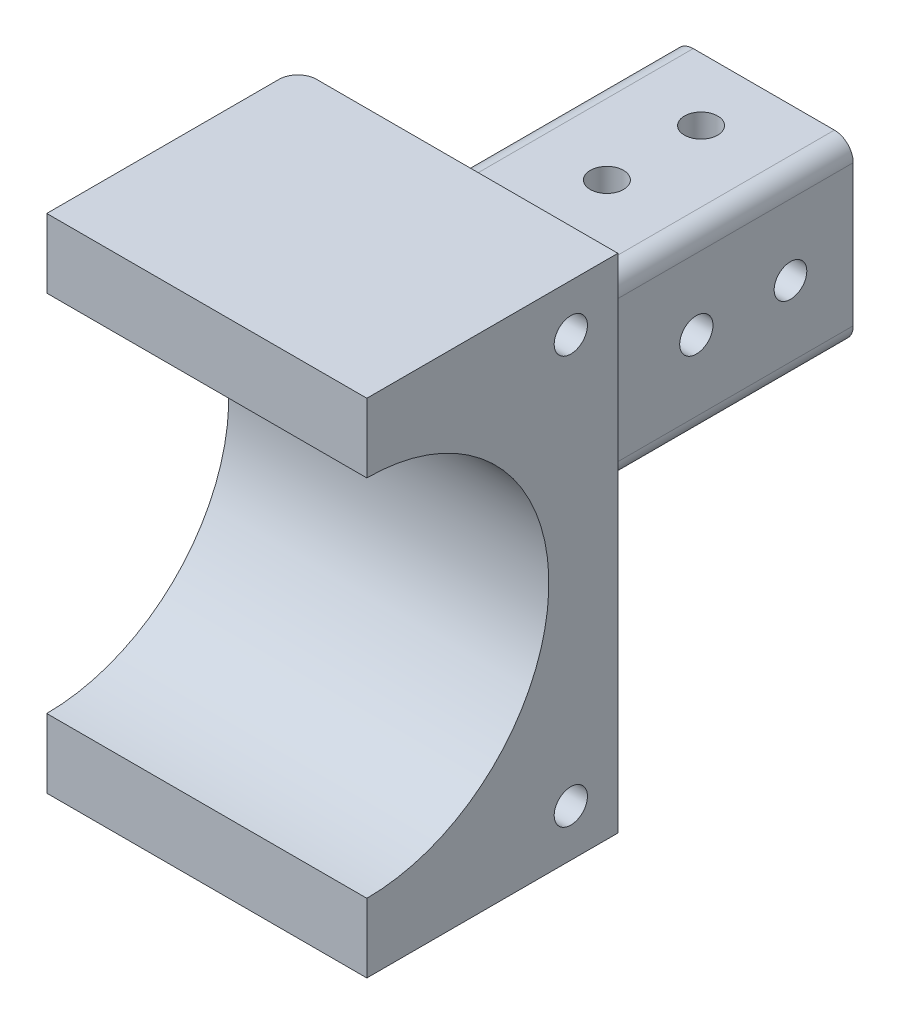
SolidWorks part; units mm, degrees
ref_plane "前视基准面" through (0, 0, 0) normal (0, 0, 1) x (1, 0, 0)
ref_plane "上视基准面" through (0, 0, 0) normal (0, 1, 0) x (1, 0, 0)
ref_plane "右视基准面" through (0, 0, 0) normal (1, 0, 0) x (0, 0, -1)
other "Configuration Table"
sketch "草图1" plane through (0, 0, 0) normal (0, 0, 1) x (1, 0, 0)
  line L0 (-14.25, 14.25) -> (14.25, 14.25)
  line L1 (-10.25, -10.25) -> (10.25, -10.25)
  line L2 (-10.25, -10.25) -> (-10.25, 10.25)
  line L3 (-10.25, 10.25) -> (10.25, 10.25)
  line L4 (10.25, -10.25) -> (10.25, 10.25)
  line L5 (-10.25, -10.25) -> (10.25, 10.25) construction
  line L6 (-10.25, 10.25) -> (10.25, -10.25) construction
  line L7 (14.25, -14.25) -> (14.25, 14.25)
  line L8 (-14.25, -14.25) -> (14.25, -14.25)
  line L9 (-14.25, -14.25) -> (-14.25, 14.25)
  point P0 (0, 0)
  dimension "D1" = 20.5
  dimension "D2" = 20.5
  dimension "D3" = 4
extrude "凸台-拉伸1" add sketch "草图1" along normal blind 30
sketch "草图2" plane through (-14.25, 0, 0) normal (-1, 0, 0) x (0, 0, 1)
  line L0 (30, 0) -> (70, 0)
  line L1 (30, 14.25) -> (30, -14.25) construction
  line L3 (110, -40) -> (30, -40)
  line L4 (110, -40) -> (110, 40)
  line L5 (110, 40) -> (30, 40)
  line L6 (30, -40) -> (30, 40)
  line L7 (110, -40) -> (30, 40) construction
  line L8 (110, 40) -> (30, -40) construction
  circle A0 centre (70, 0) radius 29
  dimension "D2" = 58
  dimension "D1" = 40
  dimension "D3" = 80
  dimension "D4" = 80
extrude "凸台-拉伸2" add sketch "草图2" against normal blind 51
fillet "圆角1" radius 22 3 edges at (0, -14.25, 30) (14.25, 0, 30) (0, 14.25, 30)
sketch "草图3" plane through (-14.25, 0, 0) normal (-1, 0, 0) x (0, 0, 1)
  line L0 (70, -40) -> (70, 40)
  line L1 (110, -40) -> (30, -40) construction
  line L2 (110, 40) -> (30, 40) construction
  line L4 (70, 40) -> (110, 40)
  line L5 (70, 40) -> (70, -40)
  line L6 (70, -40) -> (110, -40)
  line L7 (110, 40) -> (110, -40)
  line M5 (30, -40) -> (110, -40)
  line M6 (110, -40) -> (110, 40)
  line M7 (110, 40) -> (30, 40)
  circle M11 centre (70, 0) radius 29
extrude "切除-拉伸1" cut sketch "草图3" against normal blind 51 contours L0 M5 M6 M7 M11
sketch "草图5" plane through (0, 0, 0) normal (0, 0, -1) x (-1, 0, 0)
  line L1 (-10.25, -10.25) -> (10.25, -10.25)
  line L2 (-10.25, -10.25) -> (-10.25, 10.25)
  line L3 (-10.25, 10.25) -> (10.25, 10.25)
  line L4 (10.25, -10.25) -> (10.25, 10.25)
  line L5 (-10.25, -10.25) -> (10.25, 10.25) construction
  line L6 (-10.25, 10.25) -> (10.25, -10.25) construction
  line L7 (-14.25, -14.25) -> (14.25, -14.25)
  line L8 (-14.25, -14.25) -> (-14.25, 14.25)
  line L9 (-14.25, 14.25) -> (14.25, 14.25)
  line L10 (14.25, -14.25) -> (14.25, 14.25)
  line L11 (-14.25, -14.25) -> (14.25, 14.25) construction
  line L12 (-14.25, 14.25) -> (14.25, -14.25) construction
  point P0 (0, 0)
  point P7 (0, 0)
extrude "凸台-拉伸3" add sketch "草图5" along normal blind 30
sketch "草图6" plane through (14.25, 0, 0) normal (1, 0, 0) x (0, 0, -1)
  line L0 (30, 0) -> (20, 0)
  line L1 (30, 14.25) -> (30, -14.25) construction
  line L2 (20, 0) -> (5, 0)
  circle A0 centre (20, 0) radius 2.6
  circle A1 centre (5, 0) radius 2.65
  dimension "D2" = 5.2
  dimension "D4" = 5.3
  dimension "D1" = 10
  dimension "D3" = 15
extrude "切除-拉伸2" cut sketch "草图6" against normal blind 30
sketch "草图7" plane through (0, 14.25, 0) normal (0, 1, 0) x (1, 0, 0)
  line L0 (0, 30) -> (0, 20)
  line L1 (-14.25, 30) -> (14.25, 30) construction
  line L2 (0, 20) -> (0, 5)
  circle A0 centre (0, 20) radius 2.65
  circle A1 centre (0, 5) radius 2.65
  dimension "D2" = 5.3
  dimension "D4" = 5.3
  dimension "D1" = 10
  dimension "D3" = 15
extrude "切除-拉伸3" cut sketch "草图7" against normal blind 30
sketch "草图8" plane through (-14.25, 0, 0) normal (-1, 0, 0) x (0, 0, 1)
  line L1 (110, -40) -> (30, -40)
  line L2 (110, -40) -> (110, 40)
  line L3 (110, 40) -> (30, 40)
  line L4 (30, -40) -> (30, 40)
  line L5 (110, -40) -> (30, 40) construction
  line L6 (110, 40) -> (30, -40) construction
  line L7 (102.5, -32.5) -> (37.5, -32.5)
  line L8 (102.5, -32.5) -> (102.5, 32.5)
  line L9 (102.5, 32.5) -> (37.5, 32.5)
  line L10 (37.5, -32.5) -> (37.5, 32.5)
  line L11 (102.5, -32.5) -> (37.5, 32.5) construction
  line L12 (102.5, 32.5) -> (37.5, -32.5) construction
  circle A0 centre (70, 0) radius 29
  circle A1 centre (37.5, 32.5) radius 2.65
  circle A2 centre (37.5, -32.5) radius 2.65
  dimension "D2" = 5.3
  dimension "D3" = 5.3
  dimension "D1" = 65
extrude "切除-拉伸4" cut sketch "草图8" against normal through all contours A1 | A2
fillet "圆角3" radius 3 10 edges at (20.6937, -20.6937, 23.5563) (20.6937, 20.6937, 23.5563) (-14.25, -38.125, 30) (-14.25, -20.6937, 23.5563) (-14.25, 38.125, 30) (-14.25, 20.6937, 23.5563) (14.25, -14.25, -11) (14.25, 14.25, -11) (-14.25, -14.25, -11) (-14.25, 14.25, -11)
